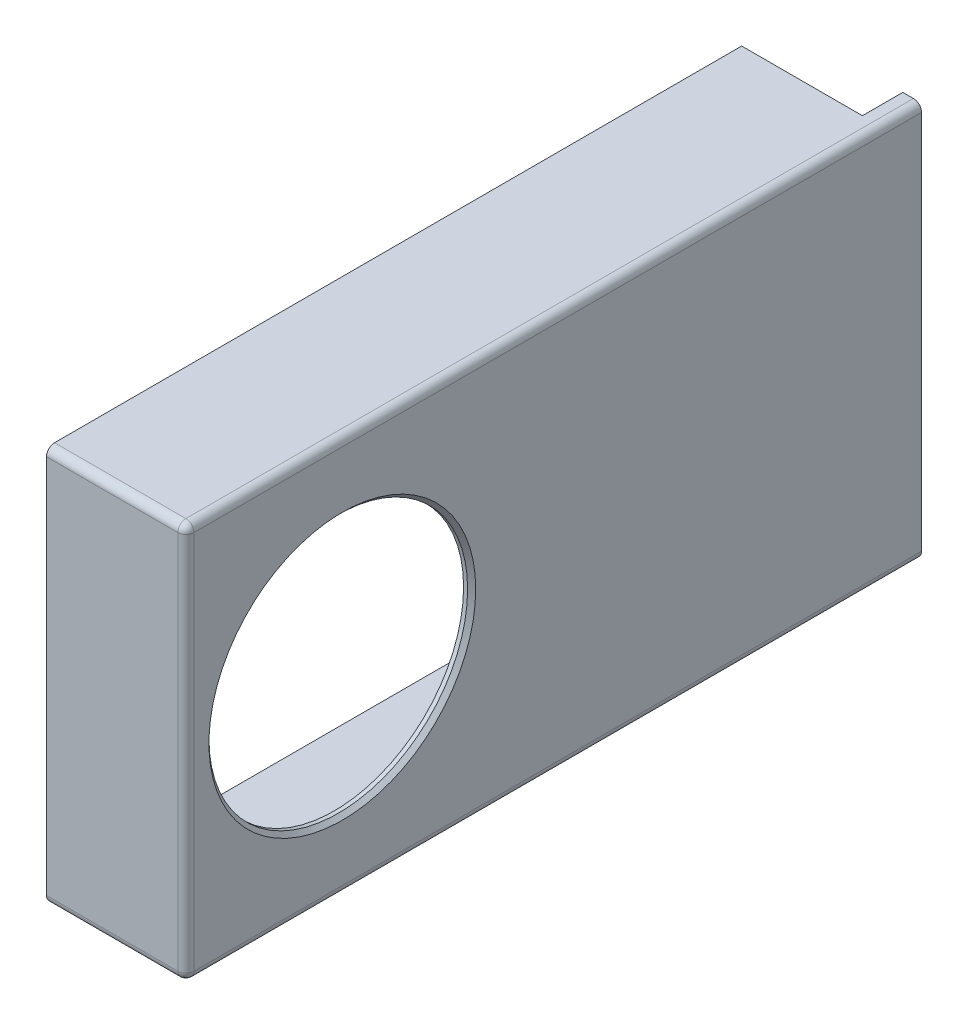
SolidWorks part; units mm, degrees
ref_plane "前视基准面" through (0, 0, 0) normal (0, 0, 1) x (1, 0, 0)
ref_plane "上视基准面" through (0, 0, 0) normal (0, 1, 0) x (1, 0, 0)
ref_plane "右视基准面" through (0, 0, 0) normal (1, 0, 0) x (0, 0, -1)
sketch "草图1" plane through (0, 0, 0) normal (1, 0, 0) x (0, 0, -1)
  line L1 (0, 0) -> (182, 0)
  line L2 (0, 0) -> (0, -98)
  line L3 (0, -98) -> (182, -98)
  line L4 (182, 0) -> (182, -98)
  dimension "D1" = 98
extrude "凸台-拉伸1" add sketch "草图1" along normal blind 34.5
shell "抽壳1" thickness 2
sketch "草图2" plane through (34.5, 0, 0) normal (1, 0, 0) x (0, 0, -1)
  line L0 (0, -49) -> (182, -49) construction
  line L1 (0, 0) -> (0, -98) construction
  line L2 (182, -98) -> (182, 0) construction
  circle A0 centre (38.6986, -49) radius 32
extrude "切除-拉伸1" cut sketch "草图2" against normal blind 10
sketch "草图3" plane through (0, 0, -182) normal (0, 0, -1) x (-1, 0, 0)
  line L1 (0, 0) -> (-29.8665, 0)
  line L2 (0, 0) -> (0, -86.6753)
  line L3 (0, -86.6753) -> (-29.8665, -86.6753)
  line L4 (-29.8665, 0) -> (-29.8665, -86.6753)
extrude "切除-拉伸2" cut sketch "草图3" against normal blind 10
fillet "圆角1" radius 2 5 edges at (34.5, 0, -91) (34.5, -98, -91) (34.5, -49, 0) (17.25, 0, 0) (17.25, -98, 0)
sketch "草图4" plane through (0, -98, 0) normal (0, -1, 0) x (-1, 0, 0)
  line L0 (0, 2) -> (0, 182) construction
  line L1 (0, 32) -> (-15, 32)
  line L2 (0, 32) -> (0, 10)
  line L3 (0, 10) -> (-15, 10)
  line L4 (-15, 32) -> (-15, 10)
  line L5 (0, 0) -> (-32.5, 0) construction
  dimension "D1" = 10
extrude "切除-拉伸3" cut sketch "草图4" against normal blind 10
fillet "圆角2" radius 1 2 edges at (15, -97, -10) (15, -97, -32)
sketch "草图5" plane through (34.5, 0, 0) normal (1, 0, 0) x (0, 0, -1)
  line L0 (172.9406, -51.9141) -> (75.9538, -51.9141) construction
  line L2 (172.9406, -37.2428) -> (77.5503, -37.2428) construction
  text T0 "RADEON PRO" font "Earth Orbiter Laser" height 7
  text T1 "OMINIS" font "Earth Orbiter Laser" height 5
extrude "凸台-拉伸2" [suppressed] add sketch "草图5" along normal blind 1
chamfer "倒角1" distance 1 angle 45 1 edges at (34.5, -49, -70.6986)
